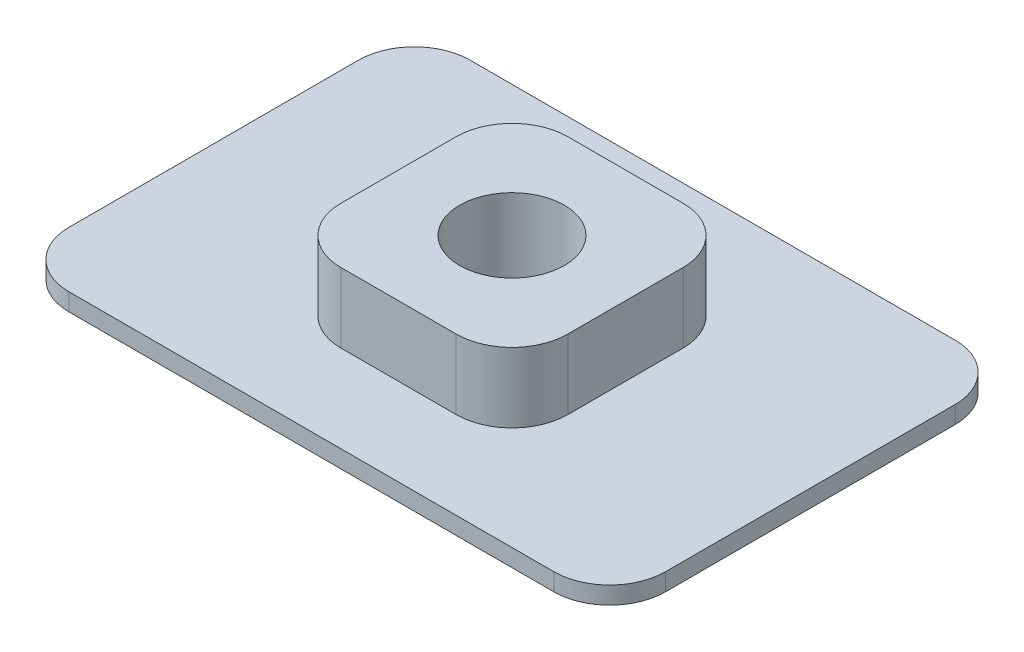
SolidWorks part; units mm, degrees
material "AISI 1020"
ref_plane "Alzado" through (0, 0, 0) normal (0, 0, 1) x (1, 0, 0)
ref_plane "Planta" through (0, 0, 0) normal (0, 1, 0) x (1, 0, 0)
ref_plane "Vista lateral" through (0, 0, 0) normal (1, 0, 0) x (0, 0, -1)
sketch "Croquis1" plane through (0, 0, 0) normal (0, 1, 0) x (1, 0, 0)
  line L1 (-42.75, -28.75) -> (42.75, -28.75)
  line L2 (-42.75, -28.75) -> (-42.75, 28.75)
  line L3 (-42.75, 28.75) -> (42.75, 28.75)
  line L4 (42.75, -28.75) -> (42.75, 28.75)
  line L5 (-42.75, -28.75) -> (42.75, 28.75) construction
  line L6 (-42.75, 28.75) -> (42.75, -28.75) construction
  point P0 (0, 0)
  dimension "D1" = 85.5
  dimension "D2" = 57.5
extrude "Saliente-Extruir1" add sketch "Croquis1" along normal blind 2.5
fillet "Redondeo1" radius 8 4 edges at (-42.75, 1.25, -28.75) (42.75, 1.25, -28.75) (42.75, 1.25, 28.75) (-42.75, 1.25, 28.75)
sketch "Croquis2" plane through (0, 2.5, 0) normal (0, 1, 0) x (1, 0, 0)
  line L1 (-16.25, -16.25) -> (16.25, -16.25)
  line L2 (-16.25, -16.25) -> (-16.25, 16.25)
  line L3 (-16.25, 16.25) -> (16.25, 16.25)
  line L4 (16.25, -16.25) -> (16.25, 16.25)
  line L5 (-16.25, -16.25) -> (16.25, 16.25) construction
  line L6 (-16.25, 16.25) -> (16.25, -16.25) construction
  point P0 (0, 0)
  dimension "D1" = 32.5
  dimension "D2" = 32.5
extrude "Saliente-Extruir2" add sketch "Croquis2" along normal blind 10
fillet "Redondeo2" radius 8 4 edges at (-16.25, 7.5, -16.25) (16.25, 7.5, -16.25) (16.25, 7.5, 16.25) (-16.25, 7.5, 16.25)
sketch "Croquis3" plane through (0, 12.5, 0) normal (0, 1, 0) x (1, 0, 0)
  circle A0 centre (0, 0) radius 7.5
  dimension "D1" = 15
extrude "Cortar-Extruir1" cut sketch "Croquis3" against normal through all
